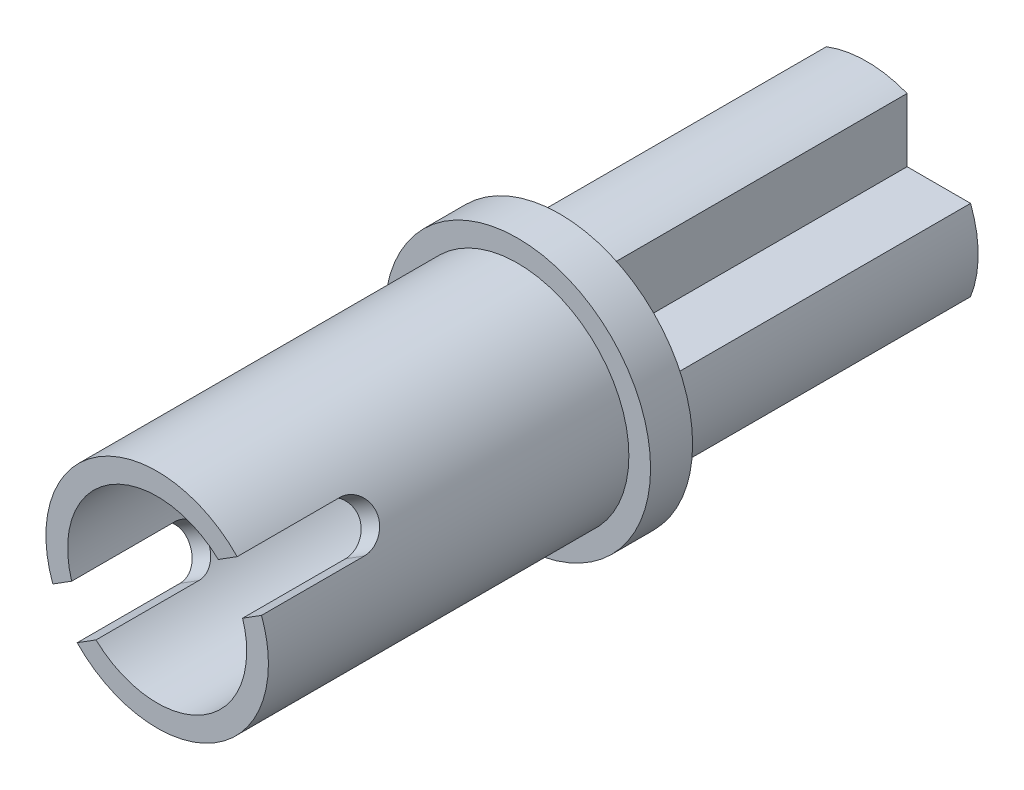
SolidWorks part; units mm, degrees
ref_plane "Front Plane" through (0, 0, 0) normal (0, 0, 1) x (1, 0, 0)
ref_plane "Top Plane" through (0, 0, 0) normal (0, 1, 0) x (1, 0, 0)
ref_plane "Right Plane" through (0, 0, 0) normal (1, 0, 0) x (0, 0, -1)
sketch "Sketch1" plane through (0, 0, 0) normal (0, 0, 1) x (1, 0, 0)
  circle A0 centre (0, 0) radius 2.91
  dimension "D1" = 5.82
extrude "Boss-Extrude1" add sketch "Sketch1" along normal blind 15.53
sketch "Sketch2" plane through (0, 0, 15.53) normal (0, 0, 1) x (1, 0, 0)
  circle A0 centre (0, 0) radius 2.435
  circle A3 centre (0, 0) radius 2.91
  circle A4 centre (0, 0) radius 2.91 construction
  dimension "D1" = 4.87
extrude "Cut-Extrude2" cut sketch "Sketch2" against normal blind 7.89
sketch "Sketch4" plane through (0, 0, 15.53) normal (0, 0, 1) x (1, 0, 0)
  circle A1 centre (0, 0) radius 1.96
  dimension "D1" = 3.92
extrude "Cut-Extrude3" cut sketch "Sketch4" against normal blind 7.89
sketch "Sketch5" plane through (0, 0, 15.53) normal (0, 0, 1) x (1, 0, 0)
  point P0 (-1.2607, -2.5701)
ref_plane "Plane2" through (-2.0617, -1.2957, 0) normal (-0.8467, -0.5321, 0) x (0, 0, 1)
sketch "Sketch6" plane through (-2.0617, -1.2957, 0) normal (-0.8467, -0.5321, 0) x (0, 0, 1)
  line L0 (15.53, 0) -> (13.28, 0) construction
  line L1 (15.53, -2.435) -> (15.53, 2.435) construction
  line L2 (15.53, -0.5) -> (13.28, -0.5)
  line L3 (15.53, 0.5) -> (13.28, 0.5)
  arc A0 (15.53, -0.5) -> (15.53, 0.5) centre (15.53, 0) ccw
  arc A1 (13.28, 0.5) -> (13.28, -0.5) centre (13.28, 0) ccw
  point P5 (14.405, 0)
  dimension "D1" = 2.25
  dimension "D2" = 1
extrude "Cut-Extrude6" cut sketch "Sketch6" against normal blind 7.89
sketch "Sketch10" plane through (0, 0, 0) normal (0, 0, -1) x (-1, 0, 0)
  line L1 (-0.885, -2.2738) -> (0.885, -2.2738)
  line L2 (-0.885, -2.2738) -> (-0.885, 2.2738)
  line L3 (-0.885, 2.2738) -> (0.885, 2.2738)
  line L4 (0.885, -2.2738) -> (0.885, 2.2738)
  line L5 (-0.885, -2.2738) -> (0.885, 2.2738) construction
  line L6 (-0.885, 2.2738) -> (0.885, -2.2738) construction
  line L7 (-2.2738, 0.885) -> (2.2738, 0.885)
  line L8 (-2.2738, 0.885) -> (-2.2738, -0.885)
  line L9 (-2.2738, -0.885) -> (2.2738, -0.885)
  line L10 (2.2738, 0.885) -> (2.2738, -0.885)
  line L11 (-2.2738, 0.885) -> (2.2738, -0.885) construction
  line L12 (-2.2738, -0.885) -> (2.2738, 0.885) construction
  circle A1 centre (0, 0) radius 2.44
  circle M6 centre (0, 0) radius 2.91
  dimension "D1" = 4.88
  dimension "D2" = 1.77
extrude "Cut-Extrude10" cut sketch "Sketch10" against normal blind 6.72 contours A1 M6 | L2 A1 L7 | L7 A1 L4 | L4 A1 L9 | L9 A1 L2
